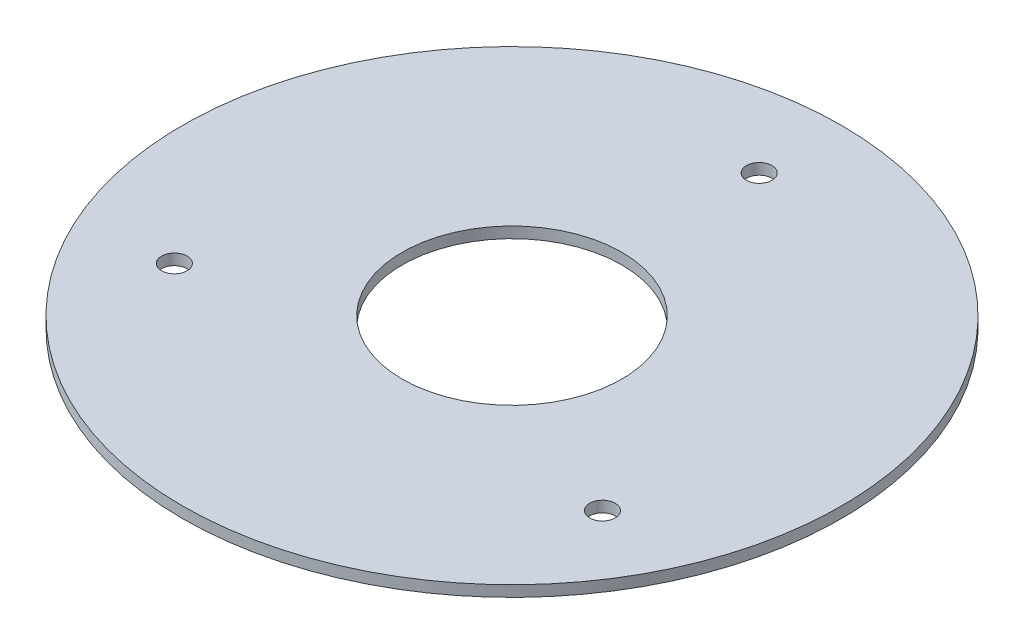
SolidWorks part; units mm, degrees
material "Acrylic (Medium-high impact)"
ref_plane "Front" through (0, 0, 0) normal (0, 0, 1) x (1, 0, 0)
ref_plane "Top" through (0, 0, 0) normal (0, 1, 0) x (1, 0, 0)
ref_plane "Right" through (0, 0, 0) normal (1, 0, 0) x (0, 0, -1)
sketch "Sketch1" plane through (0, 0, 0) normal (0, 1, 0) x (1, 0, 0)
  line L0 (0, 0) -> (0, 45.0034) construction
  circle A0 centre (0, 0) radius 60
  circle A1 centre (0, 0) radius 20
  circle A2 centre (0, 45.0034) radius 2.3231
  circle A3 centre (38.9741, -22.5017) radius 2.3231
  circle A4 centre (-38.9741, -22.5017) radius 2.3231
  point P13 (0, 0)
  dimension "D1" = 120
  dimension "D3" = 45.0034
  dimension "D4" = 4.6461
  dimension "D5" = 40
  dimension "D2" = 3
extrude "Boss-Extrude1" add sketch "Sketch1" along normal blind 2
